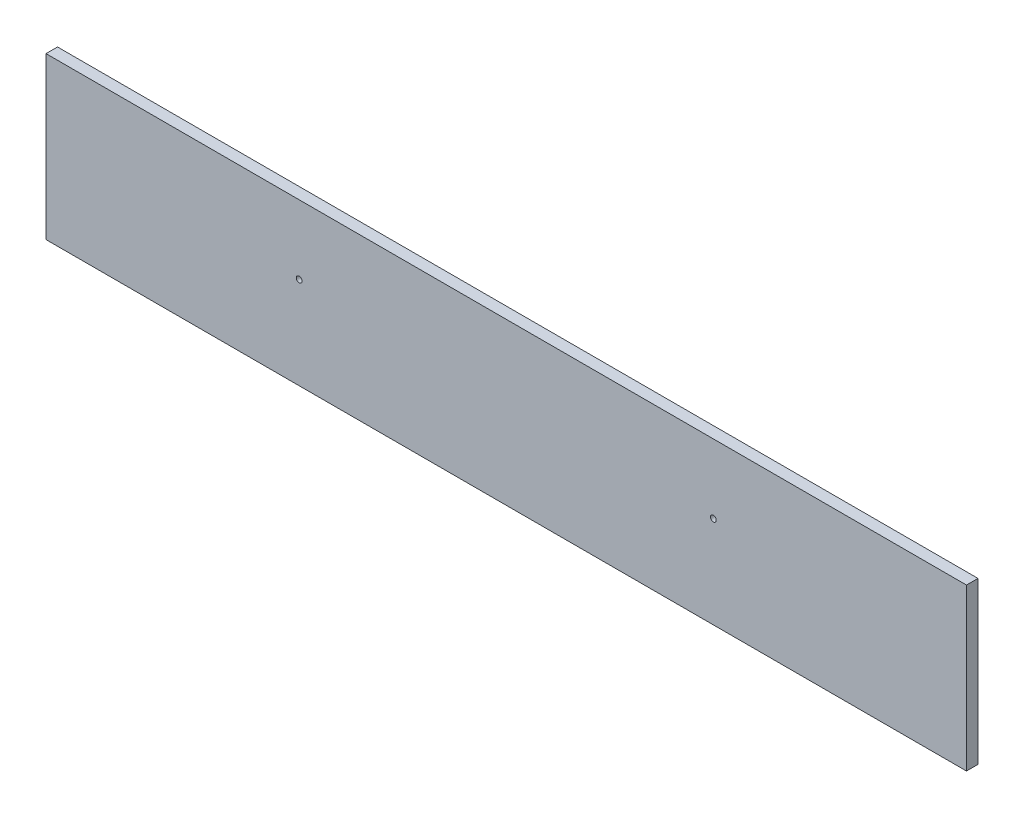
SolidWorks part; units mm, degrees
ref_plane "Front Plane" through (0, 0, 0) normal (0, 0, 1) x (1, 0, 0)
ref_plane "Top Plane" through (0, 0, 0) normal (0, 1, 0) x (1, 0, 0)
ref_plane "Right Plane" through (0, 0, 0) normal (1, 0, 0) x (0, 0, -1)
sketch "Sketch1" plane through (0, 0, 0) normal (0, 0, 1) x (1, 0, 0)
  line L0 (0, 0) -> (0, 109.663) construction
  line L1 (0, 0) -> (-113.8898, 0) construction
  line L2 (-200, -40) -> (200, -40)
  line L3 (-200, -40) -> (-200, 30)
  line L4 (-200, 30) -> (200, 30)
  line L5 (200, -40) -> (200, 30)
  line L6 (-200, -40) -> (200, 30) construction
  line L7 (-200, 30) -> (200, -40) construction
  circle A0 centre (-90, 0) radius 1.25
  circle A1 centre (90, 0) radius 1.25
  point P2 (0, -5)
  point P13 (0, 0)
  dimension "D3" = 2.5
  dimension "D4" = 90
  dimension "D1" = 400
  dimension "D2" = 70
  dimension "D5" = 5
extrude "Boss-Extrude1" add sketch "Sketch1" along normal blind 5
